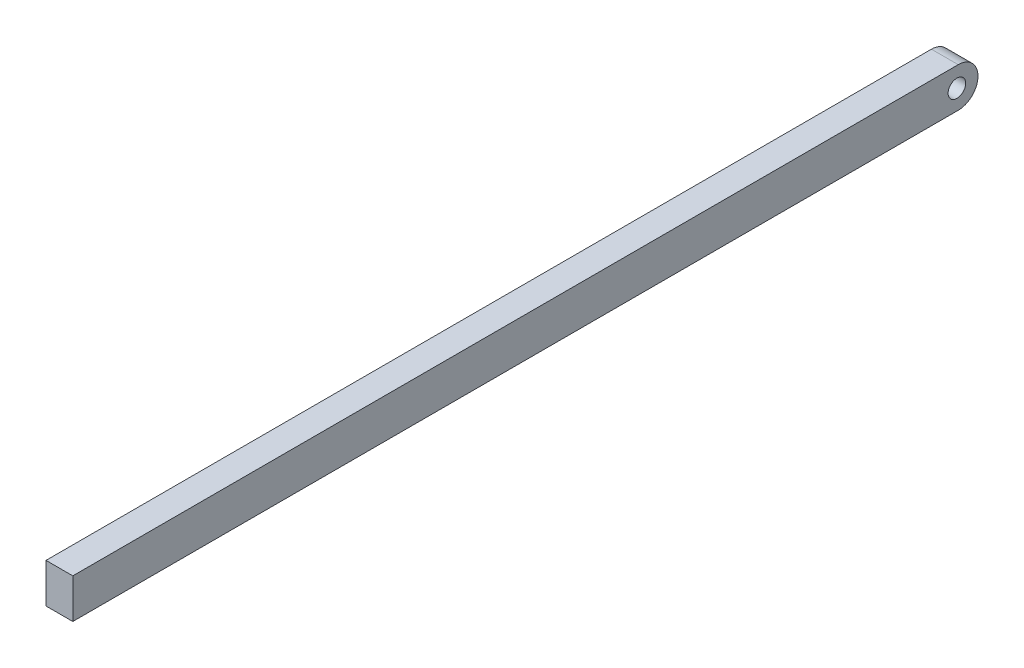
SolidWorks part; units mm, degrees
ref_plane "Front Plane" through (0, 0, 0) normal (0, 0, 1) x (1, 0, 0)
ref_plane "Top Plane" through (0, 0, 0) normal (0, 1, 0) x (1, 0, 0)
ref_plane "Right Plane" through (0, 0, 0) normal (1, 0, 0) x (0, 0, -1)
sketch "Sketch1" plane through (0, 0, 0) normal (0, 0, 1) x (1, 0, 0)
  line L1 (-3.05, -4.5) -> (3.05, -4.5)
  line L2 (-3.05, -4.5) -> (-3.05, 4.5)
  line L3 (-3.05, 4.5) -> (3.05, 4.5)
  line L4 (3.05, -4.5) -> (3.05, 4.5)
  line L5 (-3.05, -4.5) -> (3.05, 4.5) construction
  line L6 (-3.05, 4.5) -> (3.05, -4.5) construction
  point P0 (0, 0)
  dimension "D1" = 6.1
  dimension "D2" = 9
extrude "Boss-Extrude1" add sketch "Sketch1" along normal blind 9.29
sketch "Sketch3" plane through (3.05, 0, 0) normal (1, 0, 0) x (0, 0, -1)
  line L0 (0, -4.5) -> (0, 4.5) construction
  line L1 (-9.29, -4.5) -> (0, -4.5) construction
  line L2 (-9.29, 4.5) -> (0, 4.5) construction
  line L3 (-4.5, -4.5) -> (0, -4.5)
  line L4 (0, -4.5) -> (0, 4.5)
  line L5 (-4.5, 4.5) -> (0, 4.5)
  arc A0 (-4.5, -4.5) -> (-4.5, 4.5) centre (-4.5, 0) ccw
  circle A1 centre (-4.8, 0) radius 2
  line M3 (0, -4.5) -> (0, 4.5)
  line M4 (0, 4.5) -> (-9.29, 4.5)
  line M6 (-9.29, -4.5) -> (0, -4.5)
  dimension "D1" = 9
  dimension "D2" = 4
  dimension "D3" = 4.8
  dimension "D4" = 4.5
extrude "Cut-Extrude2" cut sketch "Sketch3" against normal through all contours A0 L4 M4 | A0 M6 M3 | A1
sketch "Sketch4" plane through (0, 0, 9.29) normal (0, 0, 1) x (1, 0, 0)
  line L1 (-3.05, -4.5) -> (3.05, -4.5)
  line L2 (-3.05, -4.5) -> (-3.05, 4.5)
  line L3 (-3.05, 4.5) -> (3.05, 4.5)
  line L4 (3.05, -4.5) -> (3.05, 4.5)
  line L5 (-3.05, -4.5) -> (3.05, 4.5) construction
  line L6 (-3.05, 4.5) -> (3.05, -4.5) construction
  point P0 (0, 0)
  dimension "D1" = 6.1
  dimension "D2" = 9
extrude "Boss-Extrude2" add sketch "Sketch4" along normal blind 196.7
sketch "Sketch5" plane through (0, 0, 205.99) normal (0, 0, 1) x (1, 0, 0)
  circle A0 centre (0, 0) radius 5.4362
